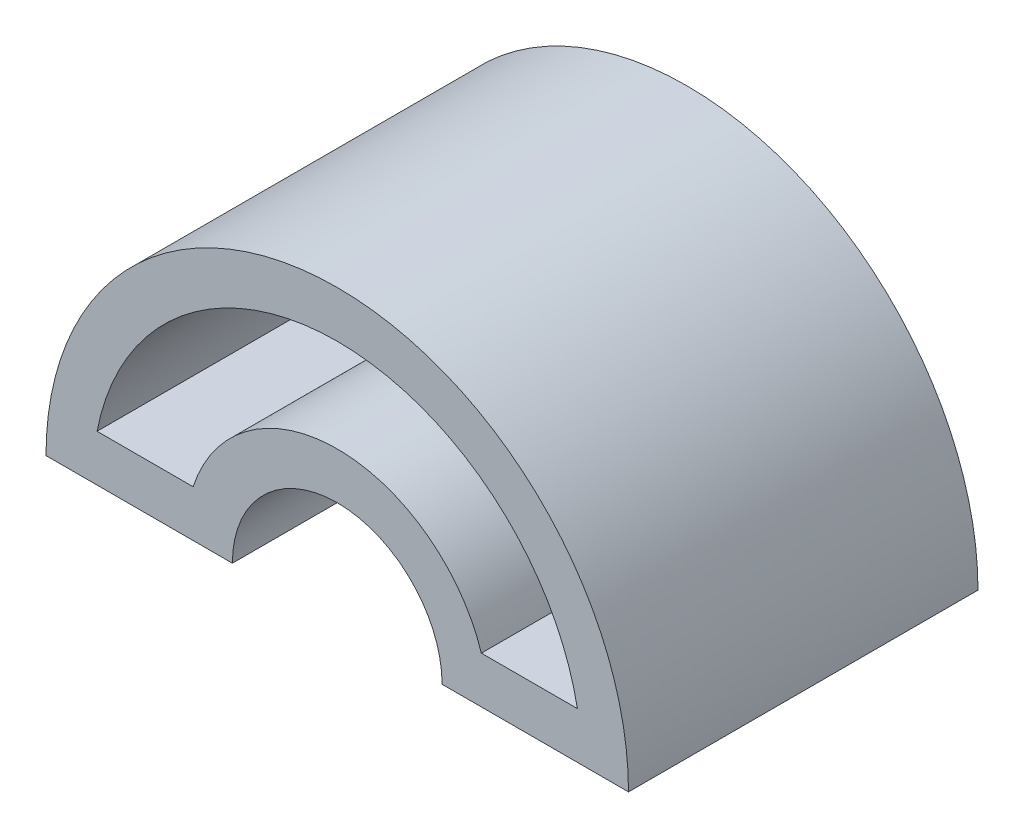
SolidWorks part; units mm, degrees
ref_plane "前视基准面" through (0, 0, 0) normal (0, 0, 1) x (1, 0, 0)
ref_plane "上视基准面" through (0, 0, 0) normal (0, 1, 0) x (1, 0, 0)
ref_plane "右视基准面" through (0, 0, 0) normal (1, 0, 0) x (0, 0, -1)
sketch "草图1" plane through (0, 0, 0) normal (0, 0, 1) x (1, 0, 0)
  line L0 (-50, 0) -> (-18, 0)
  line L1 (18, 0) -> (50, 0)
  line L2 (-41.2311, 8) -> (-24.7386, 8)
  line L4 (24.7386, 8) -> (41.2311, 8)
  arc A0 (18, 0) -> (-18, 0) centre (0, 0) ccw
  arc A1 (50, 0) -> (-50, 0) centre (0, 0) ccw
  arc A4 (41.2311, 8) -> (-41.2311, 8) centre (0, 0) ccw
  arc A5 (24.7386, 8) -> (-24.7386, 8) centre (0, 0) ccw
extrude "凸台-拉伸1" add sketch "草图1" along normal blind 60
